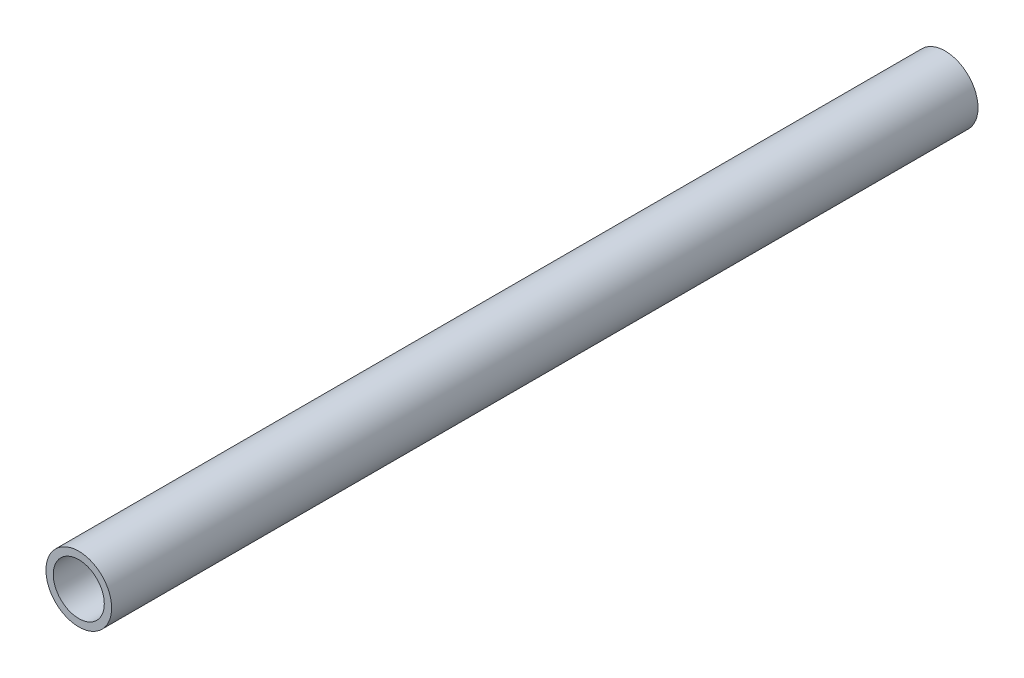
SolidWorks part; units mm, degrees
ref_plane "Front Plane" through (0, 0, 0) normal (0, 0, 1) x (1, 0, 0)
ref_plane "Top Plane" through (0, 0, 0) normal (0, 1, 0) x (1, 0, 0)
ref_plane "Right Plane" through (0, 0, 0) normal (1, 0, 0) x (0, 0, -1)
sketch "Sketch1" plane through (0, 0, 0) normal (0, 0, 1) x (1, 0, 0)
  circle A0 centre (0, 0) radius 7
  circle A1 centre (0, 0) radius 9
  dimension "D1" = 14
  dimension "D2" = 18
extrude "Boss-Extrude1" add sketch "Sketch1" along normal blind 237.54
